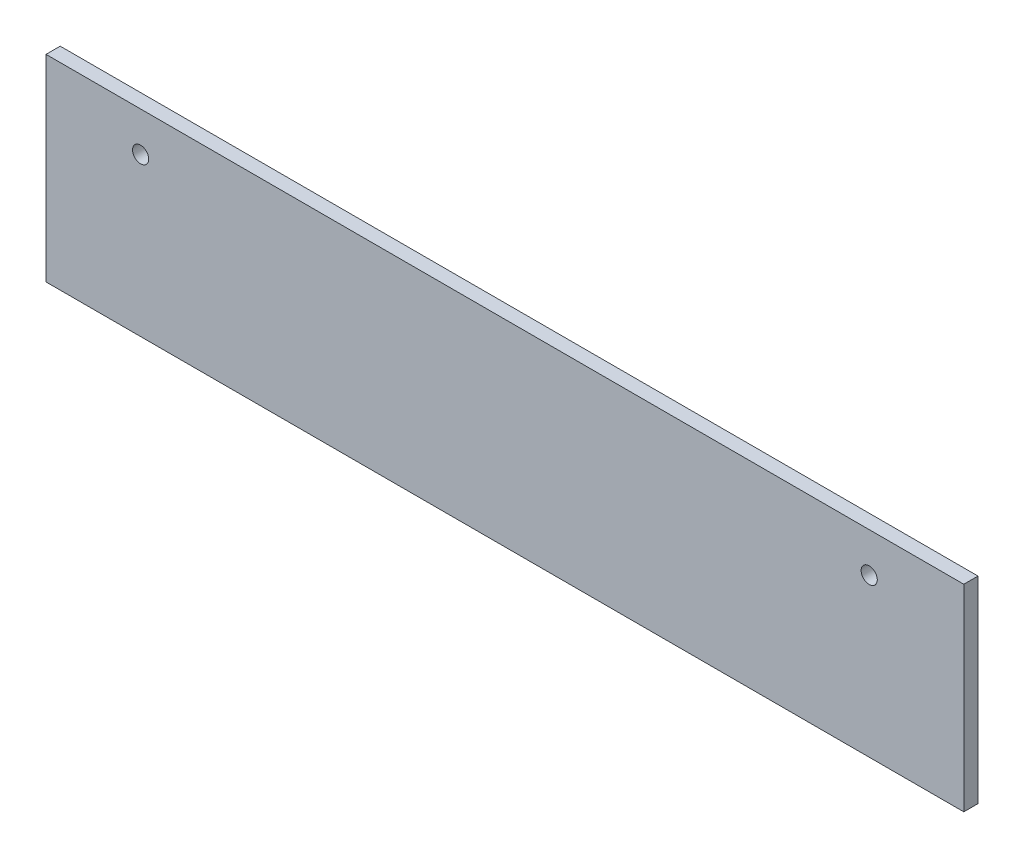
SolidWorks part; units mm, degrees
ref_plane "Plan de face" through (0, 0, 0) normal (0, 0, 1) x (1, 0, 0)
ref_plane "Plan de dessus" through (0, 0, 0) normal (0, 1, 0) x (1, 0, 0)
ref_plane "Plan de droite" through (0, 0, 0) normal (1, 0, 0) x (0, 0, -1)
sketch "Esquisse2" plane through (0, 0, 0) normal (0, 0, 1) x (1, 0, 0)
  line L0 (0, 89.4193) -> (0, -90.234) construction
  line L1 (-120, -25) -> (120, -25) construction
  line L2 (-120, -25) -> (-120, 25) construction
  line L3 (-120, 25) -> (120, 25) construction
  line L4 (120, -25) -> (120, 25) construction
  line L5 (-120, -25) -> (120, 25) construction
  line L6 (-120, 25) -> (120, -25) construction
  line L7 (116.4, -25) -> (-116.4, -25)
  line L8 (116.4, -25) -> (116.4, 25)
  line L9 (116.4, 25) -> (-116.4, 25)
  line L10 (-116.4, -25) -> (-116.4, 25)
  line L11 (116.4, -25) -> (-116.4, 25) construction
  line L12 (116.4, 25) -> (-116.4, -25) construction
  circle A0 centre (-92.4, 15) radius 2.05
  circle A1 centre (92.4, 15) radius 2.05
  point P0 (0, 0)
  point P5 (0, 0)
  point P11 (-120, 0)
  dimension "D4" = 4.1
  dimension "D1" = 240
  dimension "D2" = 50
  dimension "D3" = 3.6
  dimension "D5" = 10
  dimension "D6" = 24
extrude "Boss.-Extru.1" add sketch "Esquisse2" along normal blind 3.6
